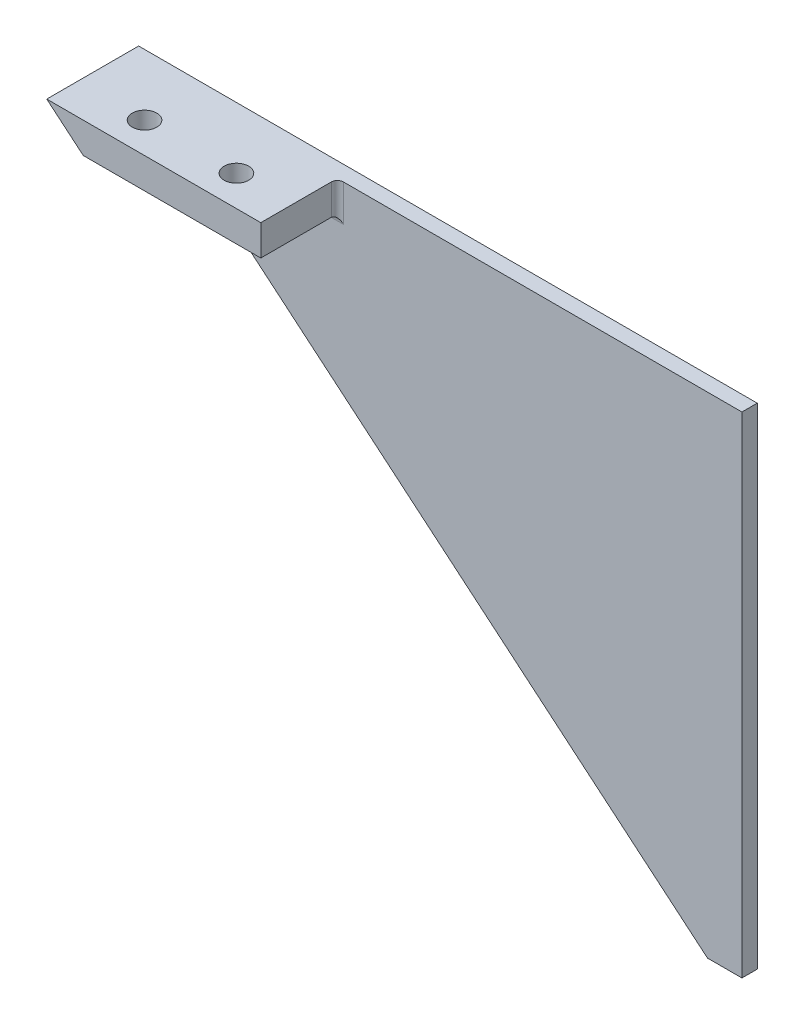
SolidWorks part; units mm, degrees
ref_plane "前视基准面" through (0, 0, 0) normal (0, 0, 1) x (1, 0, 0)
ref_plane "上视基准面" through (0, 0, 0) normal (0, 1, 0) x (1, 0, 0)
ref_plane "右视基准面" through (0, 0, 0) normal (1, 0, 0) x (0, 0, -1)
sketch "草图1" plane through (0, 0, 0) normal (0, 0, 1) x (1, 0, 0)
  line L1 (-140, 75) -> (140, 75)
  line L2 (-140, 75) -> (-140, -75)
  line L3 (-140, -75) -> (140, -75)
  line L4 (140, 75) -> (140, -75)
  line L5 (0, -75) -> (0, 75) construction
  line L6 (-140, 0) -> (140, 0) construction
  point P0 (0, 0)
  dimension "D1" = 280
  dimension "D2" = 150
extrude "凸台-拉伸1" add sketch "草图1" along normal blind 5
sketch "草图2" plane through (0, 75, 0) normal (0, 1, 0) x (1, 0, 0)
  line L0 (140, -5) -> (140, 0) construction
  line L1 (-140, -5) -> (140, -5)
  line L2 (-140, -5) -> (-140, -30)
  line L3 (-140, -30) -> (140, -30)
  line L4 (140, -5) -> (140, -30)
  point P7 (140, -2.5)
  dimension "D1" = 25
extrude "凸台-拉伸3" add sketch "草图2" against normal blind 10
sketch "草图6" plane through (0, 0, 5) normal (0, 0, 1) x (1, 0, 0)
  line L0 (154.5939, -89.8927) -> (-30, 65)
  line L1 (140, 65) -> (-140, 65) construction
  line L2 (-140, 65) -> (-140, -75) construction
  line L3 (-30, 65) -> (-77.1196, 104.538)
  line L4 (-77.1196, 104.538) -> (-170.9239, 102.0081)
  line L5 (-170.9239, 102.0081) -> (-172.6048, -51.5818)
  line L6 (-172.6048, -51.5818) -> (-172.6048, -108.5214)
  line L7 (-172.6048, -108.5214) -> (154.5939, -89.8927)
  dimension "D1" = 40
  dimension "D2" = 110
extrude "切除-拉伸1" cut sketch "草图6" against normal mid plane 1000
sketch "草图7" plane through (0, 65, 0) normal (0, -1, 0) x (1, 0, 0)
  line L0 (-30, 30) -> (-30, 5) construction
  line L1 (140, 5) -> (-30, 5) construction
  circle A0 centre (-20, 20) radius 4
  circle A1 centre (10, 20) radius 4
  dimension "D1" = 8
  dimension "D2" = 30
  dimension "D3" = 10
  dimension "D4" = 15
extrude "切除-拉伸2" cut sketch "草图7" against normal blind 1000
sketch "草图8" plane through (0, 65, 0) normal (0, -1, 0) x (1, 0, 0)
  line L0 (-30, 30) -> (140, 30) construction
  line L1 (27.9506, 30) -> (140, 30)
  line L2 (27.9506, 30) -> (27.9506, 5)
  line L3 (27.9506, 5) -> (140, 5)
  line L4 (140, 30) -> (140, 5)
extrude "切除-拉伸3" cut sketch "草图8" against normal blind 1000
sketch "草图9" plane through (140, 0, 0) normal (1, 0, 0) x (0, 0, -1)
  line L1 (-5, 75) -> (0, 75)
  line L2 (-5, 75) -> (-5, -85)
  line L3 (-5, -85) -> (0, -85)
  line L4 (0, 75) -> (0, -85)
  dimension "D1" = 160
extrude "凸台-拉伸4" add sketch "草图9" along normal blind 20
sketch "草图10" plane through (0, 0, 5) normal (0, 0, 1) x (1, 0, 0)
  line L0 (136.8455, -75) -> (140, -77.6469)
  line L1 (140, -75) -> (140, -85) construction
  line L2 (140, -77.6469) -> (140, -75)
  line L3 (140, -75) -> (136.8455, -75)
  line L4 (136.8455, -75) -> (-30, 65) construction
extrude "凸台-拉伸5" add sketch "草图10" against normal up to surface (5 mm away) up to face at (115.8213, -28.3333, 0)
sketch "草图11" plane through (0, 0, 5) normal (0, 0, 1) x (1, 0, 0)
  line L0 (140, -77.6469) -> (159.7605, -94.228)
  line L1 (159.7605, -94.228) -> (119.0276, -86.7065)
  line L2 (119.0276, -86.7065) -> (140, -77.6469)
  line L3 (140, -77.6469) -> (-30, 65) construction
extrude "切除-拉伸4" cut sketch "草图11" against normal blind 50
fillet "圆角1" radius 2 1 edges at (-1.0247, 65, 5)
fillet "圆角2" radius 2 1 edges at (27.9506, 69, 5)
